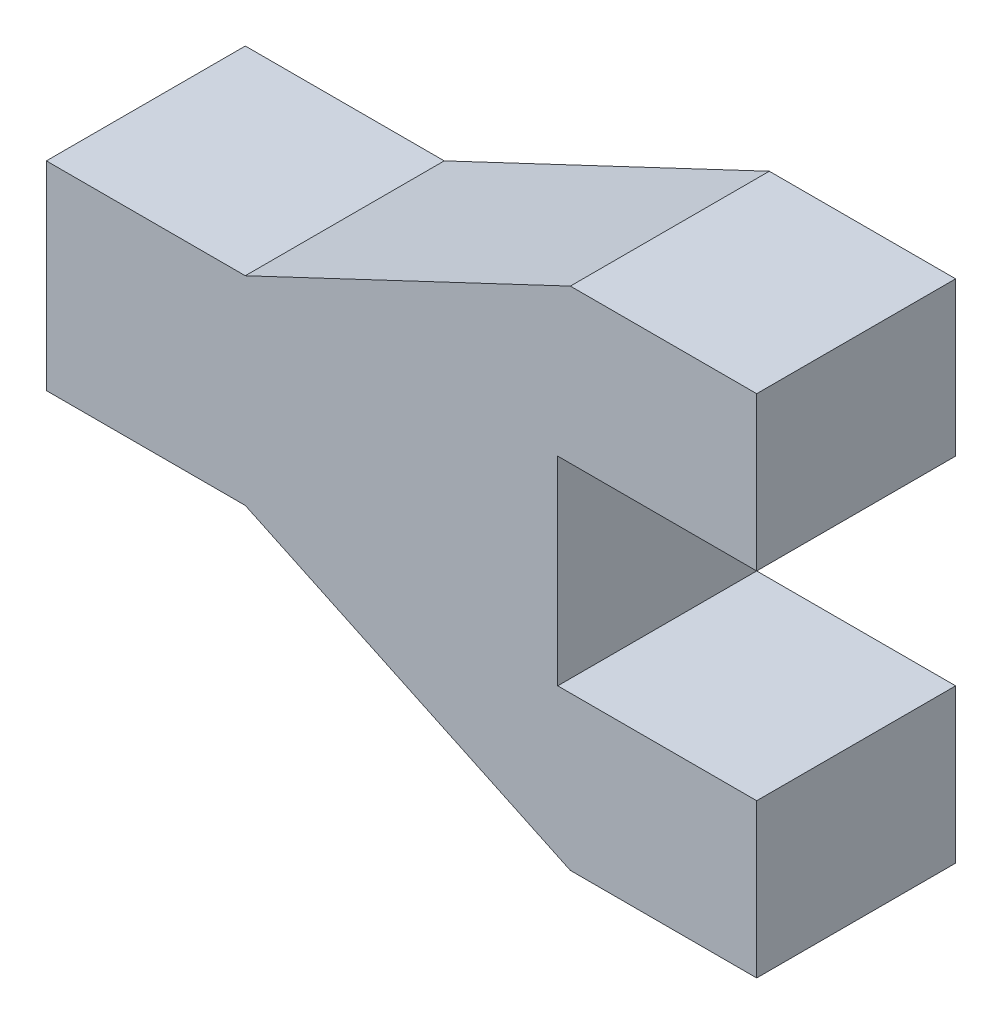
SolidWorks part; units mm, degrees
ref_plane "Front Plane" through (0, 0, 0) normal (0, 0, 1) x (1, 0, 0)
ref_plane "Top Plane" through (0, 0, 0) normal (0, 1, 0) x (1, 0, 0)
ref_plane "Right Plane" through (0, 0, 0) normal (1, 0, 0) x (0, 0, -1)
sketch "Sketch1" plane through (0, 0, 0) normal (0, 0, 1) x (1, 0, 0)
  line L0 (66.4823, -1.524) -> (66.4823, -2.7001)
  line L1 (64.9583, 0) -> (64.9583, -1.524)
  line L3 (64.9583, 0) -> (66.4823, 0)
  line L4 (64.9583, -1.524) -> (66.4823, -1.524)
  line L6 (66.4823, 0) -> (66.4823, 1.1761)
  line L7 (62.5652, 0) -> (65.0549, 1.1761)
  line L8 (65.0549, 1.1761) -> (66.4823, 1.1761)
  line L9 (65.0549, -2.7001) -> (66.4823, -2.7001)
  line L10 (62.5652, -1.524) -> (65.0549, -2.7001)
  line L11 (61.0412, -1.524) -> (61.0412, 0)
  line L12 (61.0412, 0) -> (62.5652, 0)
  line L13 (61.0412, -1.524) -> (62.5652, -1.524)
extrude "Boss-Extrude1" add sketch "Sketch1" along normal blind 1.524
